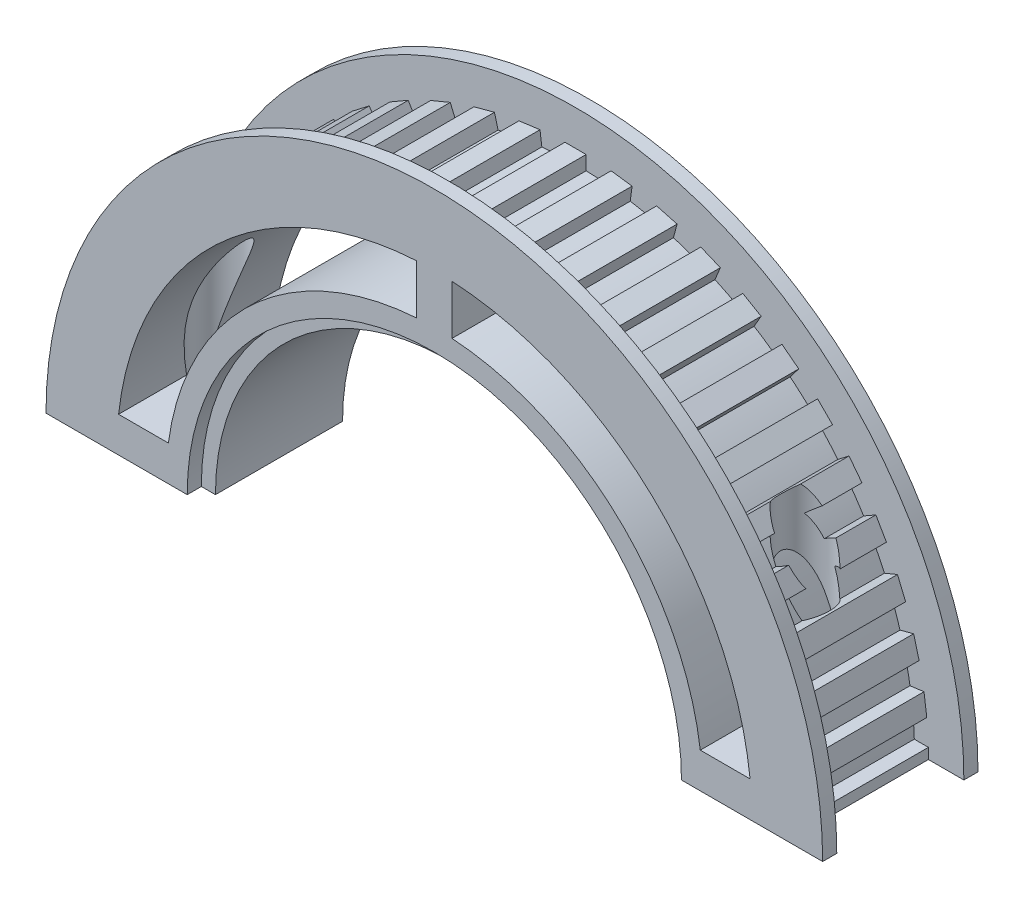
SolidWorks part; units mm, degrees
ref_plane "Front Plane" through (0, 0, 0) normal (0, 0, 1) x (1, 0, 0)
ref_plane "Top Plane" through (0, 0, 0) normal (0, 1, 0) x (1, 0, 0)
ref_plane "Right Plane" through (0, 0, 0) normal (1, 0, 0) x (0, 0, -1)
sketch "Sketch1" plane through (0, 0, 0) normal (0, 0, 1) x (1, 0, 0)
  line L0 (55, 0) -> (-55, 0) construction
  line L5 (0, -55) -> (0, 55) construction
  line L18 (-2.5, 36.9218) -> (2.5, 36.9218)
  line L19 (-2.5, 36.9218) -> (-2.5, 45.9218)
  line L20 (-2.5, 45.9218) -> (2.5, 45.9218)
  line L21 (2.5, 36.9218) -> (2.5, 45.9218)
  line L22 (-45, 0) -> (-48, 0)
  line L23 (45, 0) -> (48, 0)
  line L24 (4.775, 47.7619) -> (5.0361, 49.7448)
  line L29 (-1.5, 47.9766) -> (1.5, 47.9766)
  line L30 (-1.5, 47.9766) -> (-1.5, 49.9766)
  line L31 (-1.5, 49.9766) -> (1.5, 49.9766)
  line L32 (1.5, 47.9766) -> (1.5, 49.9766)
  line L33 (4.775, 47.7619) -> (7.7494, 47.3703)
  line L34 (7.7494, 47.3703) -> (8.0104, 49.3532)
  line L35 (5.0361, 49.7448) -> (8.0104, 49.3532)
  line L36 (10.9684, 46.73) -> (11.486, 48.6619)
  line L37 (10.9684, 46.73) -> (13.8661, 45.9536)
  line L38 (13.8661, 45.9536) -> (14.3838, 47.8854)
  line L39 (11.486, 48.6619) -> (14.3838, 47.8854)
  line L40 (16.974, 44.8986) -> (17.7394, 46.7463)
  line L41 (16.974, 44.8986) -> (19.7457, 43.7505)
  line L42 (19.7457, 43.7505) -> (20.511, 45.5983)
  line L43 (17.7394, 46.7463) -> (20.511, 45.5983)
  line L44 (22.6892, 42.2989) -> (23.6892, 44.031)
  line L45 (22.6892, 42.2989) -> (25.2873, 40.7989)
  line L46 (25.2873, 40.7989) -> (26.2873, 42.531)
  line L47 (23.6892, 44.031) -> (26.2873, 42.531)
  line L48 (28.0162, 38.9755) -> (29.2338, 40.5622)
  line L49 (28.0162, 38.9755) -> (30.3963, 37.1492)
  line L50 (30.3963, 37.1492) -> (31.6138, 38.7359)
  line L51 (29.2338, 40.5622) -> (31.6138, 38.7359)
  line L52 (32.8639, 34.9852) -> (34.2781, 36.3994)
  line L53 (32.8639, 34.9852) -> (34.9852, 32.8639)
  line L54 (34.9852, 32.8639) -> (36.3994, 34.2781)
  line L55 (34.2781, 36.3994) -> (36.3994, 34.2781)
  line L56 (37.1492, 30.3963) -> (38.7359, 31.6138)
  line L57 (37.1492, 30.3963) -> (38.9755, 28.0162)
  line L58 (38.9755, 28.0162) -> (40.5622, 29.2338)
  line L59 (38.7359, 31.6138) -> (40.5622, 29.2338)
  line L60 (40.7989, 25.2873) -> (42.531, 26.2873)
  line L61 (40.7989, 25.2873) -> (42.2989, 22.6892)
  line L62 (42.2989, 22.6892) -> (44.031, 23.6892)
  line L63 (42.531, 26.2873) -> (44.031, 23.6892)
  line L64 (43.7505, 19.7457) -> (45.5983, 20.511)
  line L65 (43.7505, 19.7457) -> (44.8986, 16.974)
  line L66 (44.8986, 16.974) -> (46.7463, 17.7394)
  line L67 (45.5983, 20.511) -> (46.7463, 17.7394)
  line L68 (45.9536, 13.8661) -> (47.8854, 14.3838)
  line L69 (45.9536, 13.8661) -> (46.73, 10.9684)
  line L70 (46.73, 10.9684) -> (48.6619, 11.486)
  line L71 (47.8854, 14.3838) -> (48.6619, 11.486)
  line L72 (47.3703, 7.7494) -> (49.3532, 8.0104)
  line L73 (47.3703, 7.7494) -> (47.7619, 4.775)
  line L74 (47.7619, 4.775) -> (49.7448, 5.0361)
  line L75 (49.3532, 8.0104) -> (49.7448, 5.0361)
  line L80 (-7.7494, 47.3703) -> (-8.0104, 49.3532)
  line L81 (-7.7494, 47.3703) -> (-4.775, 47.7619)
  line L82 (-4.775, 47.7619) -> (-5.0361, 49.7448)
  line L83 (-8.0104, 49.3532) -> (-5.0361, 49.7448)
  line L84 (-13.8661, 45.9536) -> (-14.3838, 47.8854)
  line L85 (-13.8661, 45.9536) -> (-10.9684, 46.73)
  line L86 (-10.9684, 46.73) -> (-11.486, 48.6619)
  line L87 (-14.3838, 47.8854) -> (-11.486, 48.6619)
  line L88 (-19.7457, 43.7505) -> (-20.511, 45.5983)
  line L89 (-19.7457, 43.7505) -> (-16.974, 44.8986)
  line L90 (-16.974, 44.8986) -> (-17.7394, 46.7463)
  line L91 (-20.511, 45.5983) -> (-17.7394, 46.7463)
  line L92 (-25.2873, 40.7989) -> (-26.2873, 42.531)
  line L93 (-25.2873, 40.7989) -> (-22.6892, 42.2989)
  line L94 (-22.6892, 42.2989) -> (-23.6892, 44.031)
  line L95 (-26.2873, 42.531) -> (-23.6892, 44.031)
  line L96 (-30.3963, 37.1492) -> (-31.6138, 38.7359)
  line L97 (-30.3963, 37.1492) -> (-28.0162, 38.9755)
  line L98 (-28.0162, 38.9755) -> (-29.2338, 40.5622)
  line L99 (-31.6138, 38.7359) -> (-29.2338, 40.5622)
  line L100 (-34.9852, 32.8639) -> (-36.3994, 34.2781)
  line L101 (-34.9852, 32.8639) -> (-32.8639, 34.9852)
  line L102 (-32.8639, 34.9852) -> (-34.2781, 36.3994)
  line L103 (-36.3994, 34.2781) -> (-34.2781, 36.3994)
  line L104 (-38.9755, 28.0162) -> (-40.5622, 29.2338)
  line L105 (-38.9755, 28.0162) -> (-37.1492, 30.3963)
  line L106 (-37.1492, 30.3963) -> (-38.7359, 31.6138)
  line L107 (-40.5622, 29.2338) -> (-38.7359, 31.6138)
  line L108 (-42.2989, 22.6892) -> (-44.031, 23.6892)
  line L109 (-42.2989, 22.6892) -> (-40.7989, 25.2873)
  line L110 (-40.7989, 25.2873) -> (-42.531, 26.2873)
  line L111 (-44.031, 23.6892) -> (-42.531, 26.2873)
  line L112 (-44.8986, 16.974) -> (-46.7463, 17.7394)
  line L113 (-44.8986, 16.974) -> (-43.7505, 19.7457)
  line L114 (-43.7505, 19.7457) -> (-45.5983, 20.511)
  line L115 (-46.7463, 17.7394) -> (-45.5983, 20.511)
  line L116 (-46.73, 10.9684) -> (-48.6619, 11.486)
  line L117 (-46.73, 10.9684) -> (-45.9536, 13.8661)
  line L118 (-45.9536, 13.8661) -> (-47.8854, 14.3838)
  line L119 (-48.6619, 11.486) -> (-47.8854, 14.3838)
  line L120 (-47.7619, 4.775) -> (-49.7448, 5.0361)
  line L121 (-47.7619, 4.775) -> (-47.3703, 7.7494)
  line L122 (-47.3703, 7.7494) -> (-49.3532, 8.0104)
  line L123 (-49.7448, 5.0361) -> (-49.3532, 8.0104)
  line L128 (-47.9766, -1.5) -> (-49.9766, -1.5) [skipped]
  line L129 (-49.9766, -1.5) -> (-49.9766, 1.5) [skipped]
  line L130 (-47.9766, 1.5) -> (-49.9766, 1.5) [skipped]
  line L131 (-47.9766, -1.5) -> (-47.9766, 1.5) [skipped]
  line L132 (47.9766, 1.5) -> (49.9766, 1.5) [skipped]
  line L133 (49.9766, 1.5) -> (49.9766, -1.5) [skipped]
  line L134 (47.9766, -1.5) -> (49.9766, -1.5) [skipped]
  line L135 (47.9766, 1.5) -> (47.9766, -1.5) [skipped]
  line L136 (-38, 0) -> (-35, 0)
  line L137 (47.9766, 1.5) -> (49.9766, 1.5)
  line L138 (47.9766, 1.5) -> (47.9766, 0)
  line L139 (47.9766, 0) -> (49.9766, 0)
  line L140 (49.9766, 1.5) -> (49.9766, 0)
  line L141 (-47.9766, 1.5) -> (-49.9766, 1.5)
  line L142 (-47.9766, 1.5) -> (-47.9766, 0)
  line L143 (-47.9766, 0) -> (-49.9766, 0)
  line L144 (-49.9766, 1.5) -> (-49.9766, 0)
  line L145 (35, 0) -> (38, 0)
  line L147 (-45, 0) -> (-37.4718, 0)
  line L148 (-45, 0) -> (-45, 5)
  line L149 (-45, 5) -> (-37.4718, 5)
  line L150 (-37.4718, 0) -> (-37.4718, 5)
  line L151 (45, 0) -> (37.3745, 0)
  line L152 (45, 0) -> (45, 5)
  line L153 (45, 5) -> (37.3745, 5)
  line L154 (37.3745, 0) -> (37.3745, 5)
  arc A2 (-35, 0) -> (35, 0) centre (0, 0) cw
  arc A4 (45, 0) -> (-45, 0) centre (0, 0) ccw
  arc A5 (48, 0) -> (-48, 0) centre (0, 0) ccw
  arc A6 (38, 0) -> (-38, 0) centre (0, 0) ccw
  point P81 (0, 0)
  point P131 (0, 0)
  dimension "D4" = 5
  dimension "D5" = 35
  dimension "D15" = 2
  dimension "D3" = 48
  dimension "D6" = 38
  dimension "D2" = 3
  dimension "D7" = 5
  dimension "D11" = 5
  dimension "D12" = 2.5
  dimension "D14" = 9
  dimension "D16" = 3
  dimension "D17" = 1.5
  dimension "D20" = 1.5
  dimension "D21" = 2
  dimension "D22" = 2
  dimension "D23" = 1.5
  dimension "D18" = 13
  dimension "D19" = 13
extrude "Boss-Extrude1" add sketch "Sketch1" along normal blind 22
sketch "Sketch10" plane through (0, 0, 0) normal (0, -1, 0) x (-1, 0, 0)
  line L0 (35, -22) -> (35, 0) construction
  line L1 (35, -22) -> (49.9766, -22) construction
  circle A0 centre (41.5, -11) radius 1.75
  dimension "D3" = 3.5
  dimension "D1" = 6.5
  dimension "D2" = 11
extrude "Cut-Extrude4" cut sketch "Sketch10" against normal through all
mirror "Mirror4" about plane through (0, 0, 0) normal (1, 0, 0) of "Cut-Extrude4"
sketch "Sketch5" plane through (0, 0, 0) normal (0, 0, 1) x (1, 0, 0)
  line L0 (55, 0) -> (-55, 0) construction
  line L1 (-48, 0) -> (-55, 0)
  line L2 (48, 0) -> (55, 0)
  arc A0 (48, 0) -> (-48, 0) centre (0, 0) ccw
  circle A1 centre (0, 0) radius 48 construction
  arc A2 (55, 0) -> (-55, 0) centre (0, 0) ccw
  dimension "D1" = 55
  dimension "D2" = 7
extrude "Boss-Extrude3" add sketch "Sketch5" along normal blind 2
sketch "Sketch6" plane through (0, 0, 22) normal (0, 0, 1) x (1, 0, 0)
  line L0 (55, 0) -> (-55, 0) construction
  line L1 (-45, 0) -> (-55, 0)
  line L2 (45, 0) -> (55, 0)
  arc A0 (55, 0) -> (-55, 0) centre (0, 0) ccw
  arc A1 (45, 0) -> (-45, 0) centre (0, 0) ccw
  dimension "D1" = 55
  dimension "D2" = 45
extrude "Boss-Extrude4" add sketch "Sketch6" against normal blind 2
ref_plane "Plane1" through (0, 0, 2) normal (0, 0, 1) x (1, 0, 0)
sketch "Sketch7" plane through (0, 0, 2) normal (0, 0, 1) x (1, 0, 0)
  line L0 (55, 0) -> (-55, 0) construction
  line L1 (-35, 0) -> (-33, 0)
  line L2 (33, 0) -> (35, 0)
  arc A0 (35, 0) -> (-35, 0) centre (0, 0) ccw
  arc A1 (33, 0) -> (-33, 0) centre (0, 0) ccw
  dimension "D1" = 35
  dimension "D2" = 33
extrude "Boss-Extrude5" add sketch "Sketch7" along normal blind 18
sketch "Sketch11" plane through (0, 5, 0) normal (0, 1, 0) x (1, 0, 0)
  circle A0 centre (-41.5, -11) radius 3.5
  dimension "D1" = 7
extrude "Cut-Extrude5" cut sketch "Sketch11" along normal through all
mirror "Mirror5" about plane through (0, 0, 0) normal (1, 0, 0) of "Cut-Extrude5"
sketch "Sketch12" plane through (0, 5, 0) normal (0, 1, 0) x (1, 0, 0)
  line L1 (-41.5, -14.1754) -> (-38.75, -12.5877)
  line L2 (-38.75, -12.5877) -> (-38.75, -9.4123)
  line L3 (-38.75, -9.4123) -> (-41.5, -7.8246)
  line L4 (-41.5, -7.8246) -> (-44.25, -9.4123)
  line L5 (-44.25, -9.4123) -> (-44.25, -12.5877)
  line L6 (-44.25, -12.5877) -> (-41.5, -14.1754)
  circle A0 centre (-41.5, -11) radius 2.75 construction
  dimension "D1" = 5.5
extrude "Cut-Extrude6" cut sketch "Sketch12" against normal blind 2
